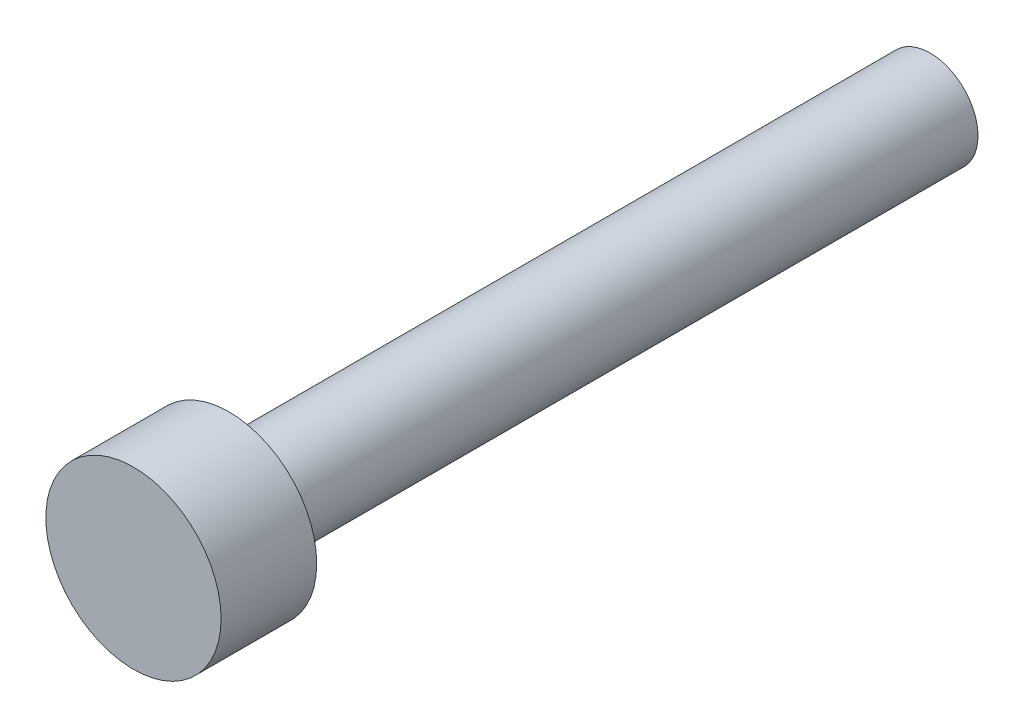
SolidWorks part; units mm, degrees
ref_plane "前视基准面" through (0, 0, 0) normal (0, 0, 1) x (1, 0, 0)
ref_plane "上视基准面" through (0, 0, 0) normal (0, 1, 0) x (1, 0, 0)
ref_plane "右视基准面" through (0, 0, 0) normal (1, 0, 0) x (0, 0, -1)
other "Configuration Table"
sketch "Sketch_Nominal_shank" plane through (0, 0, 0) normal (0, 0, 1) x (1, 0, 0)
  circle A0 centre (0, 0) radius 1.5
  dimension "D1" = 3
extrude "Nominal_shank" add sketch "Sketch_Nominal_shank" along normal blind 22 from offset 22
sketch "Sketch_Head" plane through (0, 0, 0) normal (0, 0, 1) x (1, 0, 0)
  circle A0 centre (0, 0) radius 2.75
  dimension "D1" = 5.5
extrude "Head" add sketch "Sketch_Head" along normal blind 3 from offset 0
